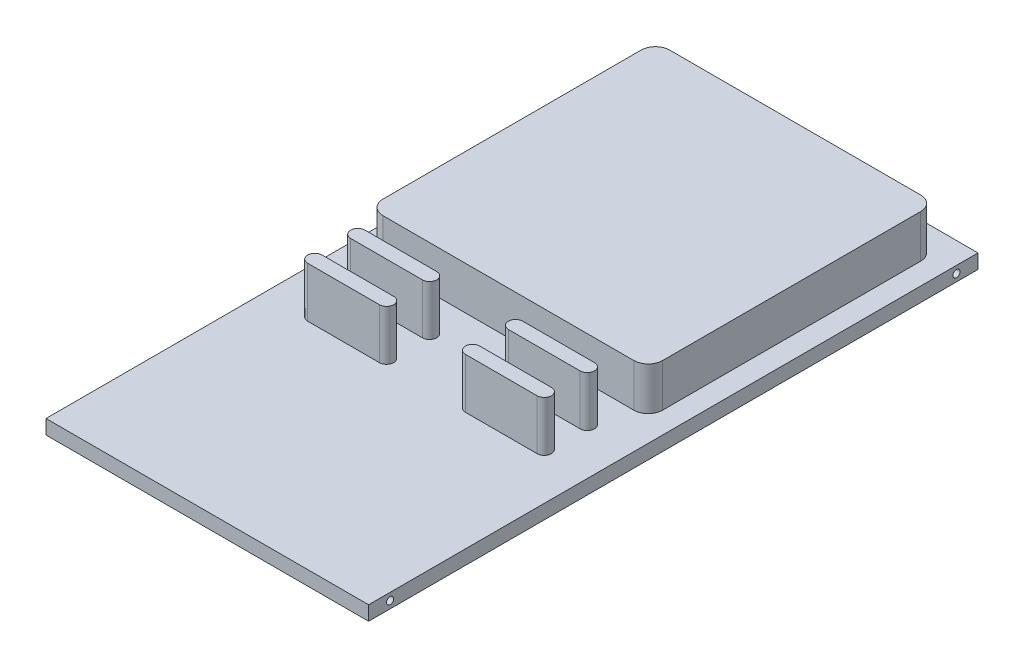
SolidWorks part; units mm, degrees
ref_plane "Front Plane" through (0, 0, 0) normal (0, 0, 1) x (1, 0, 0)
ref_plane "Top Plane" through (0, 0, 0) normal (0, 1, 0) x (1, 0, 0)
ref_plane "Right Plane" through (0, 0, 0) normal (1, 0, 0) x (0, 0, -1)
sketch "Sketch1" plane through (0, 0, 0) normal (0, 1, 0) x (1, 0, 0)
  line L1 (0, 0) -> (57.15, 0)
  line L2 (0, 0) -> (0, 107.95)
  line L3 (0, 107.95) -> (57.15, 107.95)
  line L4 (57.15, 0) -> (57.15, 107.95)
  dimension "D1" = 107.95
  dimension "D2" = 57.15
extrude "Boss-Extrude1" add sketch "Sketch1" along normal blind 2.54
sketch "Sketch2" plane through (0, 2.54, 0) normal (0, 1, 0) x (1, 0, 0)
  line L0 (0, 39.37) -> (57.15, 39.37) construction
  line L1 (0, 107.95) -> (0, 0) construction
  line L2 (57.15, 0) -> (57.15, 107.95) construction
  line L3 (0, 46.99) -> (57.15, 46.99) construction
  line L4 (0, 0) -> (57.15, 0) construction
  line L5 (28.575, 107.95) -> (28.575, 0) construction
  line L6 (57.15, 107.95) -> (0, 107.95) construction
  line L7 (8.255, 39.37) -> (20.955, 39.37) construction
  line L8 (8.255, 40.64) -> (20.955, 40.64)
  line L9 (8.255, 38.1) -> (20.955, 38.1)
  line L10 (48.895, 39.37) -> (36.195, 39.37) construction
  line L11 (48.895, 40.64) -> (36.195, 40.64)
  line L12 (48.895, 38.1) -> (36.195, 38.1)
  line L13 (8.255, 46.99) -> (20.955, 46.99) construction
  line L14 (8.255, 48.26) -> (20.955, 48.26)
  line L15 (8.255, 45.72) -> (20.955, 45.72)
  line L16 (48.895, 46.99) -> (36.195, 46.99) construction
  line L17 (48.895, 48.26) -> (36.195, 48.26)
  line L18 (48.895, 45.72) -> (36.195, 45.72)
  arc A1 (8.255, 40.64) -> (8.255, 38.1) centre (8.255, 39.37) ccw
  arc A2 (20.955, 38.1) -> (20.955, 40.64) centre (20.955, 39.37) ccw
  arc A3 (48.895, 40.64) -> (48.895, 38.1) centre (48.895, 39.37) cw
  arc A4 (36.195, 38.1) -> (36.195, 40.64) centre (36.195, 39.37) cw
  arc A5 (8.255, 48.26) -> (8.255, 45.72) centre (8.255, 46.99) ccw
  arc A6 (20.955, 45.72) -> (20.955, 48.26) centre (20.955, 46.99) ccw
  arc A7 (48.895, 48.26) -> (48.895, 45.72) centre (48.895, 46.99) cw
  arc A8 (36.195, 45.72) -> (36.195, 48.26) centre (36.195, 46.99) cw
  point P18 (14.605, 39.37)
  point P25 (42.545, 39.37)
  point P32 (14.605, 46.99)
  point P39 (42.545, 46.99)
  dimension "D1" = 39.37
  dimension "D3" = 46.99
  dimension "D4" = 14.605
  dimension "D5" = 2.54
  dimension "D6" = 12.7
  dimension "D7" = 14.605
  dimension "D8" = 12.7
  dimension "D9" = 2.54
extrude "Boss-Extrude2" add sketch "Sketch2" along normal blind 8.89
sketch "Sketch3" plane through (0, 0, 0) normal (0, 0, 1) x (1, 0, 0)
  line L0 (0, 0) -> (0, 10.16) construction
  dimension "D1" = 10.16
sketch "Sketch4" plane through (0, 0, 0) normal (-1, 0, 0) x (0, 0, 1)
  line L0 (-107.95, 1.27) -> (0, 1.27) construction
  line L1 (-107.95, 2.54) -> (-107.95, 0) construction
  line L2 (0, 0) -> (0, 10.16) construction
  line L3 (-53.975, 2.54) -> (-53.975, 0) construction
  line L4 (-107.95, 2.54) -> (0, 2.54) construction
  line L5 (-107.95, 0) -> (0, 0) construction
  circle A0 centre (-104.14, 1.27) radius 0.635
  circle A1 centre (-3.81, 1.27) radius 0.635
  dimension "D1" = 1.27
  dimension "D2" = 3.81
extrude "Cut-Extrude1" cut sketch "Sketch4" against normal blind 10.16
ref_plane "Plane1" through (28.575, 0, 0) normal (-1, 0, 0) x (0, 0, 1)
mirror "Mirror1" about plane through (28.575, 0, 0) normal (-1, 0, 0) of "Cut-Extrude1"
sketch "Sketch5" plane through (0, 2.54, 0) normal (0, 1, 0) x (1, 0, 0)
  line L0 (0, 78.74) -> (57.15, 78.74) construction
  line L1 (0, 107.95) -> (0, 0) construction
  line L2 (57.15, 0) -> (57.15, 107.95) construction
  line L3 (57.15, 107.95) -> (0, 107.95) construction
  line L5 (3.81, 53.34) -> (53.34, 53.34)
  line L6 (3.81, 53.34) -> (3.81, 104.14)
  line L7 (3.81, 104.14) -> (53.34, 104.14)
  line L8 (53.34, 53.34) -> (53.34, 104.14)
  line L9 (3.81, 53.34) -> (53.34, 104.14) construction
  line L10 (3.81, 104.14) -> (53.34, 53.34) construction
  point P8 (28.575, 78.74)
  dimension "D2" = 3.81
  dimension "D1" = 29.21
  dimension "D3" = 3.81
extrude "Boss-Extrude3" add sketch "Sketch5" along normal blind 7.62
fillet "Fillet1" radius 2.54 4 edges at (53.34, 6.35, -53.34) (53.34, 6.35, -104.14) (3.81, 6.35, -104.14) (3.81, 6.35, -53.34)
